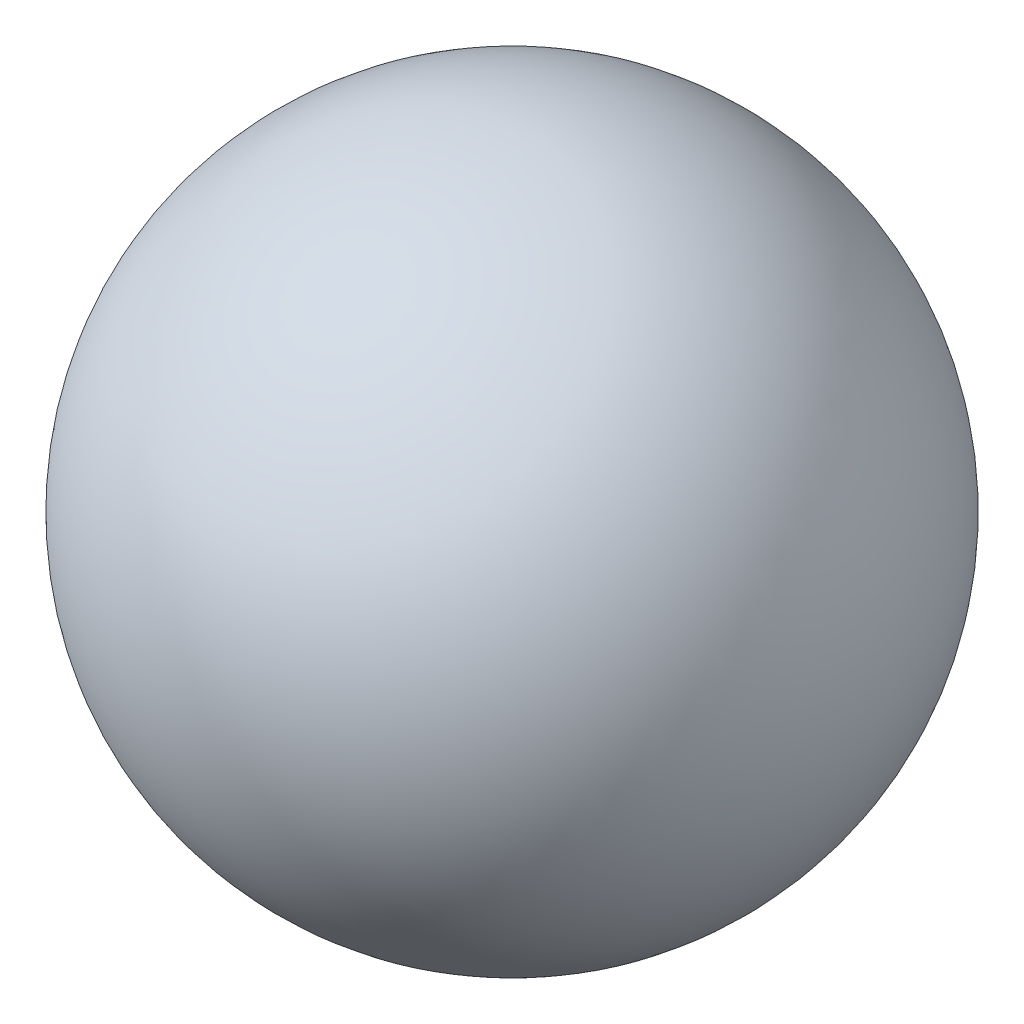
SolidWorks part; units mm, degrees
ref_plane "Front Plane" through (0, 0, 0) normal (0, 0, 1) x (1, 0, 0)
ref_plane "Top Plane" through (0, 0, 0) normal (0, 1, 0) x (1, 0, 0)
ref_plane "Right Plane" through (0, 0, 0) normal (1, 0, 0) x (0, 0, -1)
sketch "Sketch1" plane through (0, 0, 0) normal (0, 0, 1) x (1, 0, 0)
  line L0 (0, 50.8) -> (0, -50.8)
  arc A0 (0, -50.8) -> (0, 50.8) centre (0, 0) ccw
  dimension "D1" = 101.6
revolve "Revolve1" add sketch "Sketch1" angle 360 about L0
